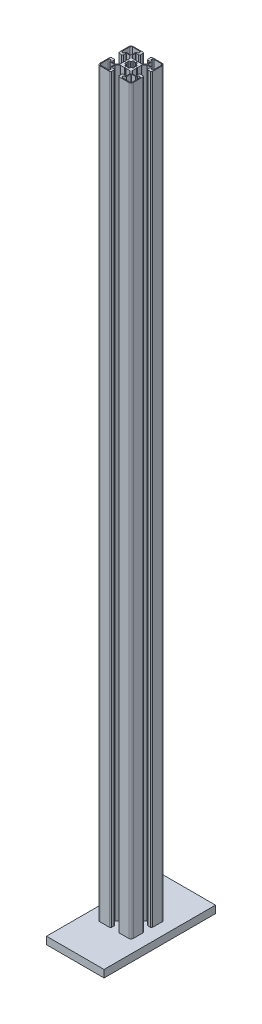
SolidWorks part; units mm, degrees
material "Commercially Pure CP-Ti UNS R50400 (SS)"
ref_plane "Front Plane" through (0, 0, 0) normal (0, 0, 1) x (1, 0, 0)
ref_plane "Top Plane" through (0, 0, 0) normal (0, 1, 0) x (1, 0, 0)
ref_plane "Right Plane" through (0, 0, 0) normal (1, 0, 0) x (0, 0, -1)
sketch "Sketch1" plane through (0, 0, 0) normal (0, 1, 0) x (1, 0, 0)
  line L0 (13.9698, 21.2743) -> (13.5298, 21.2743)
  line L1 (12.0298, 22.7743) -> (12.0298, 23.2743)
  line L2 (13.5298, 24.7743) -> (23.1398, 24.7743)
  line L3 (25.4198, 22.4943) -> (25.4198, 12.8843)
  line L4 (23.9198, 11.3843) -> (23.4198, 11.3843)
  line L5 (21.9198, 12.8843) -> (21.9198, 13.3243)
  line L6 (20.9198, 14.3243) -> (15.3498, 14.3243)
  line L7 (14.9698, 14.7043) -> (14.9698, 20.2743)
  line L8 (21.9589, -6.6897) -> (21.9589, -6.2497)
  line L9 (23.4589, -4.7497) -> (23.9589, -4.7497)
  line L10 (25.4589, -6.2497) -> (25.4589, -15.8597)
  line L11 (23.1789, -18.1397) -> (13.5689, -18.1397)
  line L12 (12.0689, -16.6397) -> (12.0689, -16.1397)
  line L13 (13.5689, -14.6397) -> (14.0089, -14.6397)
  line L14 (15.0089, -13.6397) -> (15.0089, -8.0697)
  line L15 (15.3889, -7.6897) -> (20.9589, -7.6897)
  line L16 (-6.0052, -14.6787) -> (-5.5652, -14.6787)
  line L17 (-4.0652, -16.1787) -> (-4.0652, -16.6787)
  line L18 (-5.5652, -18.1787) -> (-15.1752, -18.1787)
  line L19 (-17.4552, -15.8987) -> (-17.4552, -6.2887)
  line L20 (-15.9552, -4.7887) -> (-15.4552, -4.7887)
  line L21 (-13.9552, -6.2887) -> (-13.9552, -6.7287)
  line L22 (-12.9552, -7.7287) -> (-7.3852, -7.7287)
  line L23 (-7.0052, -8.1087) -> (-7.0052, -13.6787)
  line L24 (1.8289, -2.4886) -> (1.4132, -2.3164)
  line L25 (-1.632, 0.7289) -> (-1.8042, 1.1447)
  line L26 (-1.804, 5.4512) -> (-1.6318, 5.867)
  line L27 (1.4134, 8.9121) -> (1.8292, 9.0843)
  line L28 (6.1358, 9.0842) -> (6.5515, 8.912)
  line L29 (9.5966, 5.8667) -> (9.7688, 5.451)
  line L30 (9.7687, 1.1444) -> (9.5965, 0.7287)
  line L31 (6.5512, -2.3165) -> (6.1355, -2.4887)
  line L32 (-13.9942, 13.2853) -> (-13.9942, 12.8453)
  line L33 (-15.4942, 11.3453) -> (-15.9942, 11.3453)
  line L34 (-17.4942, 12.8453) -> (-17.4942, 22.4553)
  line L35 (-15.2142, 24.7353) -> (-5.6042, 24.7353)
  line L36 (-4.1042, 23.2353) -> (-4.1042, 22.7353)
  line L37 (-5.6042, 21.2353) -> (-6.0442, 21.2353)
  line L38 (-7.0442, 20.2353) -> (-7.0442, 14.6653)
  line L39 (-7.4242, 14.2853) -> (-12.9942, 14.2853)
  line L40 (4.9058, 11.2153) -> (4.0058, 10.7002)
  line L41 (4.0058, 10.7002) -> (3.1058, 11.2153)
  line L42 (3.1058, 11.2153) -> (-2.1975, 11.2153)
  line L43 (-2.4662, 11.3266) -> (-5.9329, 14.7933)
  line L44 (-6.0442, 15.062) -> (-6.0442, 19.3553)
  line L45 (-5.6642, 19.7353) -> (-2.5792, 19.7353)
  line L46 (-1.0592, 21.2553) -> (-1.0592, 24.2153)
  line L47 (-2.5792, 25.7353) -> (-15.4942, 25.7353)
  line L48 (-18.4942, 22.7353) -> (-18.4942, 9.8203)
  line L49 (-16.9742, 8.3003) -> (-14.0142, 8.3003)
  line L50 (-12.4942, 9.8203) -> (-12.4942, 12.9053)
  line L51 (-12.1142, 13.2853) -> (-7.8138, 13.2853)
  line L52 (-7.5451, 13.174) -> (-4.0855, 9.7144)
  line L53 (-3.9742, 9.4457) -> (-3.9742, 4.1353)
  line L54 (-3.9742, 4.1353) -> (-3.4546, 3.2353)
  line L55 (-3.4546, 3.2353) -> (-3.9742, 2.3353)
  line L56 (-3.9742, 2.3353) -> (-3.9742, -2.968)
  line L57 (-4.0855, -3.2367) -> (-7.5522, -6.7034)
  line L58 (-7.8209, -6.8147) -> (-12.1142, -6.8147)
  line L59 (-12.4942, -6.4347) -> (-12.4942, -3.3497)
  line L60 (-14.0142, -1.8297) -> (-16.9742, -1.8297)
  line L61 (-18.4942, -3.3497) -> (-18.4942, -16.2647)
  line L62 (-15.4942, -19.2647) -> (-2.5792, -19.2647)
  line L63 (-1.0592, -17.7447) -> (-1.0592, -14.7847)
  line L64 (-2.5792, -13.2647) -> (-5.6642, -13.2647)
  line L65 (-6.0442, -12.8847) -> (-6.0442, -8.5843)
  line L66 (-5.9329, -8.3156) -> (-2.4733, -4.856)
  line L67 (-2.2046, -4.7447) -> (3.1058, -4.7447)
  line L68 (3.1058, -4.7447) -> (4.0058, -4.2295)
  line L69 (4.0058, -4.2295) -> (4.9058, -4.7447)
  line L70 (4.9058, -4.7447) -> (10.2091, -4.7447)
  line L71 (10.4778, -4.856) -> (13.9445, -8.3227)
  line L72 (14.0558, -8.5914) -> (14.0558, -12.8847)
  line L73 (13.6758, -13.2647) -> (10.5908, -13.2647)
  line L74 (9.0708, -14.7847) -> (9.0708, -17.7447)
  line L75 (10.5908, -19.2647) -> (23.5058, -19.2647)
  line L76 (26.5058, -16.2647) -> (26.5058, -3.3497)
  line L77 (24.9858, -1.8297) -> (22.0258, -1.8297)
  line L78 (20.5058, -3.3497) -> (20.5058, -6.4347)
  line L79 (20.1258, -6.8147) -> (15.8254, -6.8147)
  line L80 (15.5567, -6.7034) -> (12.0971, -3.2438)
  line L81 (11.9858, -2.9751) -> (11.9858, 2.3353)
  line L82 (11.9858, 2.3353) -> (11.4662, 3.2353)
  line L83 (11.4662, 3.2353) -> (11.9858, 4.1353)
  line L84 (11.9858, 4.1353) -> (11.9858, 9.4386)
  line L85 (12.0971, 9.7073) -> (15.5638, 13.174)
  line L86 (15.8325, 13.2853) -> (20.1258, 13.2853)
  line L87 (20.5058, 12.9053) -> (20.5058, 9.8203)
  line L88 (22.0258, 8.3003) -> (24.9858, 8.3003)
  line L89 (26.5058, 9.8203) -> (26.5058, 22.7353)
  line L90 (23.5058, 25.7353) -> (10.5908, 25.7353)
  line L91 (9.0708, 24.2153) -> (9.0708, 21.2553)
  line L92 (10.5908, 19.7353) -> (13.6758, 19.7353)
  line L93 (14.0558, 19.3553) -> (14.0558, 15.0549)
  line L94 (13.9445, 14.7862) -> (10.4849, 11.3266)
  line L95 (10.2162, 11.2153) -> (4.9058, 11.2153)
  arc A0 (14.9698, 20.2743) -> (13.9698, 21.2743) centre (13.9698, 20.2743) ccw
  arc A1 (12.0298, 22.7743) -> (13.5298, 21.2743) centre (13.5298, 22.7743) ccw
  arc A2 (13.5298, 24.7743) -> (12.0298, 23.2743) centre (13.5298, 23.2743) ccw
  arc A3 (25.4198, 22.4943) -> (23.1398, 24.7743) centre (23.1398, 22.4943) ccw
  arc A4 (23.9198, 11.3843) -> (25.4198, 12.8843) centre (23.9198, 12.8843) ccw
  arc A5 (21.9198, 12.8843) -> (23.4198, 11.3843) centre (23.4198, 12.8843) ccw
  arc A6 (21.9198, 13.3243) -> (20.9198, 14.3243) centre (20.9198, 13.3243) ccw
  arc A7 (14.9698, 14.7043) -> (15.3498, 14.3243) centre (15.3498, 14.7043) ccw
  arc A8 (20.9589, -7.6897) -> (21.9589, -6.6897) centre (20.9589, -6.6897) ccw
  arc A9 (23.4589, -4.7497) -> (21.9589, -6.2497) centre (23.4589, -6.2497) ccw
  arc A10 (25.4589, -6.2497) -> (23.9589, -4.7497) centre (23.9589, -6.2497) ccw
  arc A11 (23.1789, -18.1397) -> (25.4589, -15.8597) centre (23.1789, -15.8597) ccw
  arc A12 (12.0689, -16.6397) -> (13.5689, -18.1397) centre (13.5689, -16.6397) ccw
  arc A13 (13.5689, -14.6397) -> (12.0689, -16.1397) centre (13.5689, -16.1397) ccw
  arc A14 (14.0089, -14.6397) -> (15.0089, -13.6397) centre (14.0089, -13.6397) ccw
  arc A15 (15.3889, -7.6897) -> (15.0089, -8.0697) centre (15.3889, -8.0697) ccw
  arc A16 (-7.0052, -13.6787) -> (-6.0052, -14.6787) centre (-6.0052, -13.6787) ccw
  arc A17 (-4.0652, -16.1787) -> (-5.5652, -14.6787) centre (-5.5652, -16.1787) ccw
  arc A18 (-5.5652, -18.1787) -> (-4.0652, -16.6787) centre (-5.5652, -16.6787) ccw
  arc A19 (-17.4552, -15.8987) -> (-15.1752, -18.1787) centre (-15.1752, -15.8987) ccw
  arc A20 (-15.9552, -4.7887) -> (-17.4552, -6.2887) centre (-15.9552, -6.2887) ccw
  arc A21 (-13.9552, -6.2887) -> (-15.4552, -4.7887) centre (-15.4552, -6.2887) ccw
  arc A22 (-13.9552, -6.7287) -> (-12.9552, -7.7287) centre (-12.9552, -6.7287) ccw
  arc A23 (-7.0052, -8.1087) -> (-7.3852, -7.7287) centre (-7.3852, -8.1087) ccw
  arc A24 (1.0363, -0.7421) -> (1.4132, -2.3164) centre (1.7959, -1.3925) ccw
  arc A25 (-0.0577, 0.352) -> (1.0363, -0.7421) centre (3.9823, 3.2978) ccw
  arc A26 (-1.632, 0.7289) -> (-0.0577, 0.352) centre (-0.7081, 1.1116) ccw
  arc A27 (-0.9575, 2.5244) -> (-1.8042, 1.1447) centre (-0.8803, 1.5274) ccw
  arc A28 (-0.9574, 4.0715) -> (-0.9575, 2.5244) centre (3.9823, 3.2978) ccw
  arc A29 (-1.804, 5.4512) -> (-0.9574, 4.0715) centre (-0.8802, 5.0686) ccw
  arc A30 (-0.0575, 6.2439) -> (-1.6318, 5.867) centre (-0.708, 5.4843) ccw
  arc A31 (1.0365, 7.3379) -> (-0.0575, 6.2439) centre (3.9823, 3.2978) ccw
  arc A32 (1.4134, 8.9121) -> (1.0365, 7.3379) centre (1.7961, 7.9882) ccw
  arc A33 (3.2089, 8.2376) -> (1.8292, 9.0843) centre (2.2119, 8.1604) ccw
  arc A34 (4.7561, 8.2376) -> (3.2089, 8.2376) centre (3.9823, 3.2978) ccw
  arc A35 (6.1358, 9.0842) -> (4.7561, 8.2376) centre (5.7531, 8.1603) ccw
  arc A36 (6.9284, 7.3377) -> (6.5515, 8.912) centre (6.1688, 7.9881) ccw
  arc A37 (8.0224, 6.2437) -> (6.9284, 7.3377) centre (3.9823, 3.2978) ccw
  arc A38 (9.5966, 5.8667) -> (8.0224, 6.2437) centre (8.6727, 5.484) ccw
  arc A39 (8.9222, 4.0713) -> (9.7688, 5.451) centre (8.845, 5.0683) ccw
  arc A40 (8.9221, 2.5241) -> (8.9222, 4.0713) centre (3.9823, 3.2978) ccw
  arc A41 (9.7687, 1.1444) -> (8.9221, 2.5241) centre (8.8448, 1.5271) ccw
  arc A42 (8.0222, 0.3518) -> (9.5965, 0.7287) centre (8.6726, 1.1113) ccw
  arc A43 (6.9282, -0.7422) -> (8.0222, 0.3518) centre (3.9823, 3.2978) ccw
  arc A44 (6.5512, -2.3165) -> (6.9282, -0.7422) centre (6.1685, -1.3926) ccw
  arc A45 (4.7558, -1.642) -> (6.1355, -2.4887) centre (5.7528, -1.5648) ccw
  arc A46 (3.2086, -1.642) -> (4.7558, -1.642) centre (3.9823, 3.2978) ccw
  arc A47 (1.8289, -2.4886) -> (3.2086, -1.642) centre (2.2116, -1.5647) ccw
  arc A48 (-12.9942, 14.2853) -> (-13.9942, 13.2853) centre (-12.9942, 13.2853) ccw
  arc A49 (-15.4942, 11.3453) -> (-13.9942, 12.8453) centre (-15.4942, 12.8453) ccw
  arc A50 (-17.4942, 12.8453) -> (-15.9942, 11.3453) centre (-15.9942, 12.8453) ccw
  arc A51 (-15.2142, 24.7353) -> (-17.4942, 22.4553) centre (-15.2142, 22.4553) ccw
  arc A52 (-4.1042, 23.2353) -> (-5.6042, 24.7353) centre (-5.6042, 23.2353) ccw
  arc A53 (-5.6042, 21.2353) -> (-4.1042, 22.7353) centre (-5.6042, 22.7353) ccw
  arc A54 (-6.0442, 21.2353) -> (-7.0442, 20.2353) centre (-6.0442, 20.2353) ccw
  arc A55 (-7.4242, 14.2853) -> (-7.0442, 14.6653) centre (-7.4242, 14.6653) ccw
  arc A56 (-2.4662, 11.3266) -> (-2.1975, 11.2153) centre (-2.1975, 11.5953) ccw
  arc A57 (-6.0442, 15.062) -> (-5.9329, 14.7933) centre (-5.6642, 15.062) ccw
  arc A58 (-5.6642, 19.7353) -> (-6.0442, 19.3553) centre (-5.6642, 19.3553) ccw
  arc A59 (-2.5792, 19.7353) -> (-1.0592, 21.2553) centre (-2.5792, 21.2553) ccw
  arc A60 (-1.0592, 24.2153) -> (-2.5792, 25.7353) centre (-2.5792, 24.2153) ccw
  arc A61 (-15.4942, 25.7353) -> (-18.4942, 22.7353) centre (-15.4942, 22.7353) ccw
  arc A62 (-18.4942, 9.8203) -> (-16.9742, 8.3003) centre (-16.9742, 9.8203) ccw
  arc A63 (-14.0142, 8.3003) -> (-12.4942, 9.8203) centre (-14.0142, 9.8203) ccw
  arc A64 (-12.1142, 13.2853) -> (-12.4942, 12.9053) centre (-12.1142, 12.9053) ccw
  arc A65 (-7.5451, 13.174) -> (-7.8138, 13.2853) centre (-7.8138, 12.9053) ccw
  arc A66 (-3.9742, 9.4457) -> (-4.0855, 9.7144) centre (-4.3542, 9.4457) ccw
  arc A67 (-4.0855, -3.2367) -> (-3.9742, -2.968) centre (-4.3542, -2.968) ccw
  arc A68 (-7.8209, -6.8147) -> (-7.5522, -6.7034) centre (-7.8209, -6.4347) ccw
  arc A69 (-12.4942, -6.4347) -> (-12.1142, -6.8147) centre (-12.1142, -6.4347) ccw
  arc A70 (-12.4942, -3.3497) -> (-14.0142, -1.8297) centre (-14.0142, -3.3497) ccw
  arc A71 (-16.9742, -1.8297) -> (-18.4942, -3.3497) centre (-16.9742, -3.3497) ccw
  arc A72 (-18.4942, -16.2647) -> (-15.4942, -19.2647) centre (-15.4942, -16.2647) ccw
  arc A73 (-2.5792, -19.2647) -> (-1.0592, -17.7447) centre (-2.5792, -17.7447) ccw
  arc A74 (-1.0592, -14.7847) -> (-2.5792, -13.2647) centre (-2.5792, -14.7847) ccw
  arc A75 (-6.0442, -12.8847) -> (-5.6642, -13.2647) centre (-5.6642, -12.8847) ccw
  arc A76 (-5.9329, -8.3156) -> (-6.0442, -8.5843) centre (-5.6642, -8.5843) ccw
  arc A77 (-2.2046, -4.7447) -> (-2.4733, -4.856) centre (-2.2046, -5.1247) ccw
  arc A78 (10.4778, -4.856) -> (10.2091, -4.7447) centre (10.2091, -5.1247) ccw
  arc A79 (14.0558, -8.5914) -> (13.9445, -8.3227) centre (13.6758, -8.5914) ccw
  arc A80 (13.6758, -13.2647) -> (14.0558, -12.8847) centre (13.6758, -12.8847) ccw
  arc A81 (10.5908, -13.2647) -> (9.0708, -14.7847) centre (10.5908, -14.7847) ccw
  arc A82 (9.0708, -17.7447) -> (10.5908, -19.2647) centre (10.5908, -17.7447) ccw
  arc A83 (23.5058, -19.2647) -> (26.5058, -16.2647) centre (23.5058, -16.2647) ccw
  arc A84 (26.5058, -3.3497) -> (24.9858, -1.8297) centre (24.9858, -3.3497) ccw
  arc A85 (22.0258, -1.8297) -> (20.5058, -3.3497) centre (22.0258, -3.3497) ccw
  arc A86 (20.1258, -6.8147) -> (20.5058, -6.4347) centre (20.1258, -6.4347) ccw
  arc A87 (15.5567, -6.7034) -> (15.8254, -6.8147) centre (15.8254, -6.4347) ccw
  arc A88 (11.9858, -2.9751) -> (12.0971, -3.2438) centre (12.3658, -2.9751) ccw
  arc A89 (12.0971, 9.7073) -> (11.9858, 9.4386) centre (12.3658, 9.4386) ccw
  arc A90 (15.8325, 13.2853) -> (15.5638, 13.174) centre (15.8325, 12.9053) ccw
  arc A91 (20.5058, 12.9053) -> (20.1258, 13.2853) centre (20.1258, 12.9053) ccw
  arc A92 (20.5058, 9.8203) -> (22.0258, 8.3003) centre (22.0258, 9.8203) ccw
  arc A93 (24.9858, 8.3003) -> (26.5058, 9.8203) centre (24.9858, 9.8203) ccw
  arc A94 (26.5058, 22.7353) -> (23.5058, 25.7353) centre (23.5058, 22.7353) ccw
  arc A95 (10.5908, 25.7353) -> (9.0708, 24.2153) centre (10.5908, 24.2153) ccw
  arc A96 (9.0708, 21.2553) -> (10.5908, 19.7353) centre (10.5908, 21.2553) ccw
  arc A97 (14.0558, 19.3553) -> (13.6758, 19.7353) centre (13.6758, 19.3553) ccw
  arc A98 (13.9445, 14.7862) -> (14.0558, 15.0549) centre (13.6758, 15.0549) ccw
  arc A99 (10.2162, 11.2153) -> (10.4849, 11.3266) centre (10.2162, 11.5953) ccw
extrude "Extrude1" add sketch "Sketch1" along normal blind 1000
sketch "Sketch2" plane through (0, 0, 0) normal (0, -1, 0) x (1, 0, 0)
  line L113 (-34.6909, 72.1105) -> (42.9602, 72.1105)
  line L114 (-34.6909, 72.1105) -> (-34.6909, -78.2194)
  line L115 (-34.6909, -78.2194) -> (42.9602, -78.2194)
  line L116 (42.9602, 72.1105) -> (42.9602, -78.2194)
  line L117 (-34.6909, 72.1105) -> (42.9602, -78.2194) construction
  line L118 (-34.6909, -78.2194) -> (42.9602, 72.1105) construction
  point P7 (4.1347, -3.0544)
extrude "Boss-Extrude1" add sketch "Sketch2" along normal blind 10
